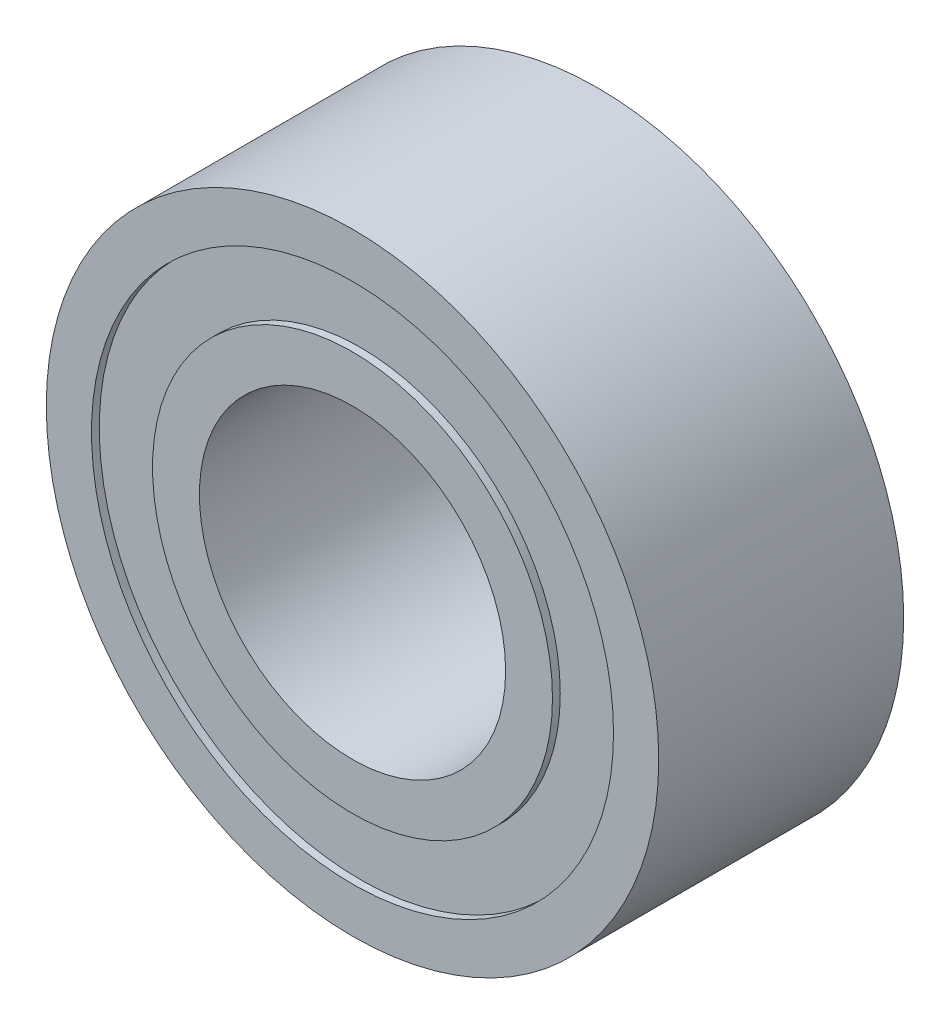
SolidWorks part; units mm, degrees
material "Chrome Stainless Steel"
ref_plane "Front Plane" through (0, 0, 0) normal (0, 0, 1) x (1, 0, 0)
ref_plane "Top Plane" through (0, 0, 0) normal (0, 1, 0) x (1, 0, 0)
ref_plane "Right Plane" through (0, 0, 0) normal (1, 0, 0) x (0, 0, -1)
sketch "Sketch1" plane through (0, 0, 0) normal (0, 0, 1) x (1, 0, 0)
  circle A0 centre (0, 0) radius 2.5
  circle A1 centre (0, 0) radius 5
  dimension "D1" = 10
  dimension "D2" = 5
extrude "Boss-Extrude1" add sketch "Sketch1" along normal blind 4
sketch "Sketch2" plane through (0, 0, 4) normal (0, 0, 1) x (1, 0, 0)
  circle A0 centre (0, 0) radius 3.2653
  circle A1 centre (0, 0) radius 4.2616
extrude "Cut-Extrude1" cut sketch "Sketch2" against normal blind 0.127
sketch "Sketch3" plane through (0, 0, 0) normal (0, 0, -1) x (-1, 0, 0)
  circle A0 centre (0, 0) radius 4.2616 construction
  circle A1 centre (0, 0) radius 3.2653 construction
  circle A2 centre (0, 0) radius 4.2616
  circle A3 centre (0, 0) radius 3.2653
extrude "Cut-Extrude2" cut sketch "Sketch3" against normal blind 0.127
